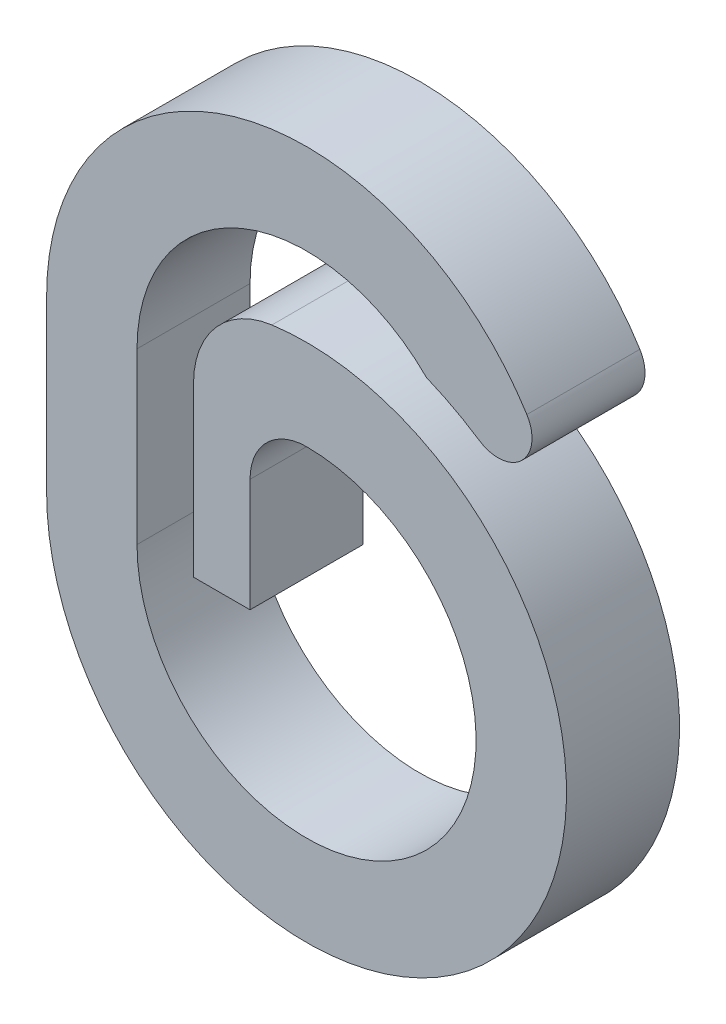
SolidWorks part; units mm, degrees
ref_plane "Front Plane" through (0, 0, 0) normal (0, 0, 1) x (1, 0, 0)
ref_plane "Top Plane" through (0, 0, 0) normal (0, 1, 0) x (1, 0, 0)
ref_plane "Right Plane" through (0, 0, 0) normal (1, 0, 0) x (0, 0, -1)
sketch "Sketch1" plane through (0, 0, 0) normal (0, 0, 1) x (1, 0, 0)
  line L0 (-23, 0) -> (-23, 15)
  line L1 (-10, 11.1803) -> (-10, 0)
  line L2 (-10, 0) -> (-5, 0)
  line L3 (-5, 0) -> (-5, 10)
  line L4 (-10, 14.8661) -> (-10, 11.1803)
  line L5 (-15, 15) -> (-15, 0)
  arc A0 (-15, 0) -> (0, 15) centre (0, 0) ccw
  arc A1 (-23, 0) -> (-3.0667, 22.7946) centre (0, 0) ccw
  arc A3 (10.6066, 25.6066) -> (-15, 15) centre (0, 15) ccw
  arc A4 (0, 15) -> (-5, 10) centre (0, 10) ccw
  arc A5 (-10, 14.8661) -> (-3.0667, 22.7946) centre (-2, 14.8661) cw
  circle A6 centre (0, 0) radius 23 construction
  arc A7 (15.2942, 23.1146) -> (10.6066, 25.6066) centre (0, 0) ccw
  arc A8 (19.492, 27.209) -> (-23, 15) centre (0, 15) ccw
  arc A9 (15.2942, 23.1146) -> (19.492, 27.209) centre (16.9496, 25.6165) ccw
  circle A10 centre (0, 0) radius 15 construction
  point P1 (0, 0)
  point P19 (-10, 20.7123)
  dimension "D1" = 15
  dimension "D4" = 27.7164
  dimension "D6" = 3
  dimension "D2" = 23
  dimension "D3" = 5
  dimension "D5" = 8
extrude "Boss-Extrude1" add sketch "Sketch1" along normal blind 10
